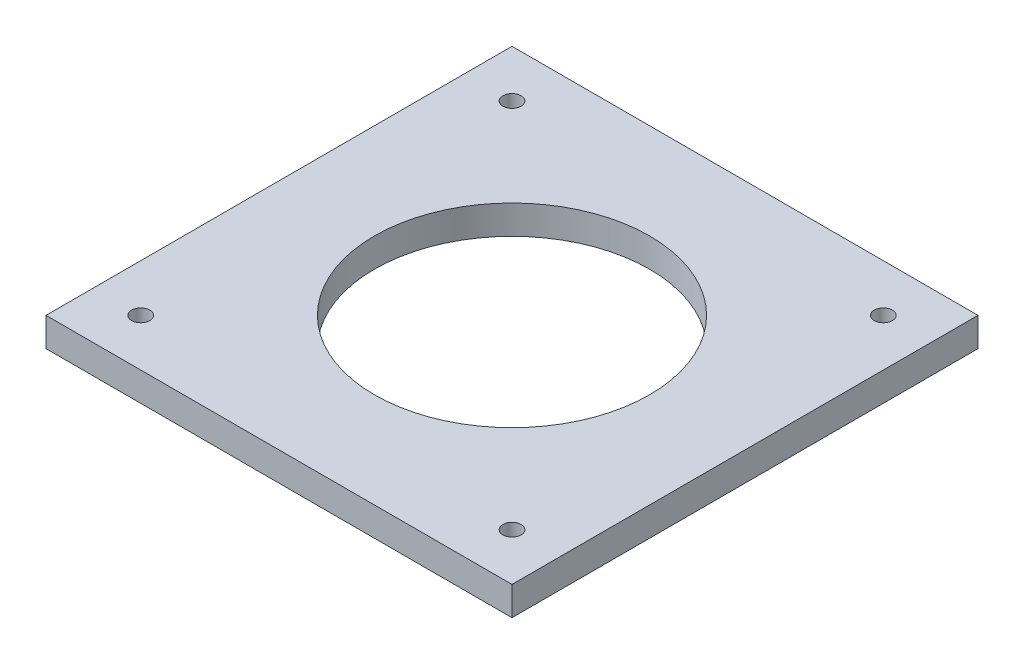
SolidWorks part; units mm, degrees
material "Rubber"
ref_plane "Front Plane" through (0, 0, 0) normal (0, 0, 1) x (1, 0, 0)
ref_plane "Top Plane" through (0, 0, 0) normal (0, 1, 0) x (1, 0, 0)
ref_plane "Right Plane" through (0, 0, 0) normal (1, 0, 0) x (0, 0, -1)
sketch "Sketch1" plane through (0, 0, 0) normal (0, 1, 0) x (1, 0, 0)
  line L1 (-50.8, 50.8) -> (50.8, 50.8)
  line L2 (-50.8, 50.8) -> (-50.8, -50.8)
  line L3 (-50.8, -50.8) -> (50.8, -50.8)
  line L4 (50.8, 50.8) -> (50.8, -50.8)
  line L5 (-50.8, 50.8) -> (50.8, -50.8) construction
  line L6 (-50.8, -50.8) -> (50.8, 50.8) construction
  line L7 (-40.48, 40.48) -> (40.48, 40.48) construction
  line L8 (-40.48, 40.48) -> (-40.48, -40.48) construction
  line L9 (-40.48, -40.48) -> (40.48, -40.48) construction
  line L10 (40.48, 40.48) -> (40.48, -40.48) construction
  circle A0 centre (0, 0) radius 30
  circle A1 centre (-40.48, 40.48) radius 1.985
  circle A2 centre (40.48, 40.48) radius 1.985
  circle A3 centre (40.48, -40.48) radius 1.985
  circle A4 centre (-40.48, -40.48) radius 1.985
  point P4 (0, 0)
  point P23 (0, 0)
  dimension "D2" = 60
  dimension "D4" = 3.97
  dimension "D1" = 101.6
  dimension "D3" = 80.96
  dimension "D5" = 4
extrude "Boss-Extrude1" add sketch "Sketch1" along normal blind 6.29
